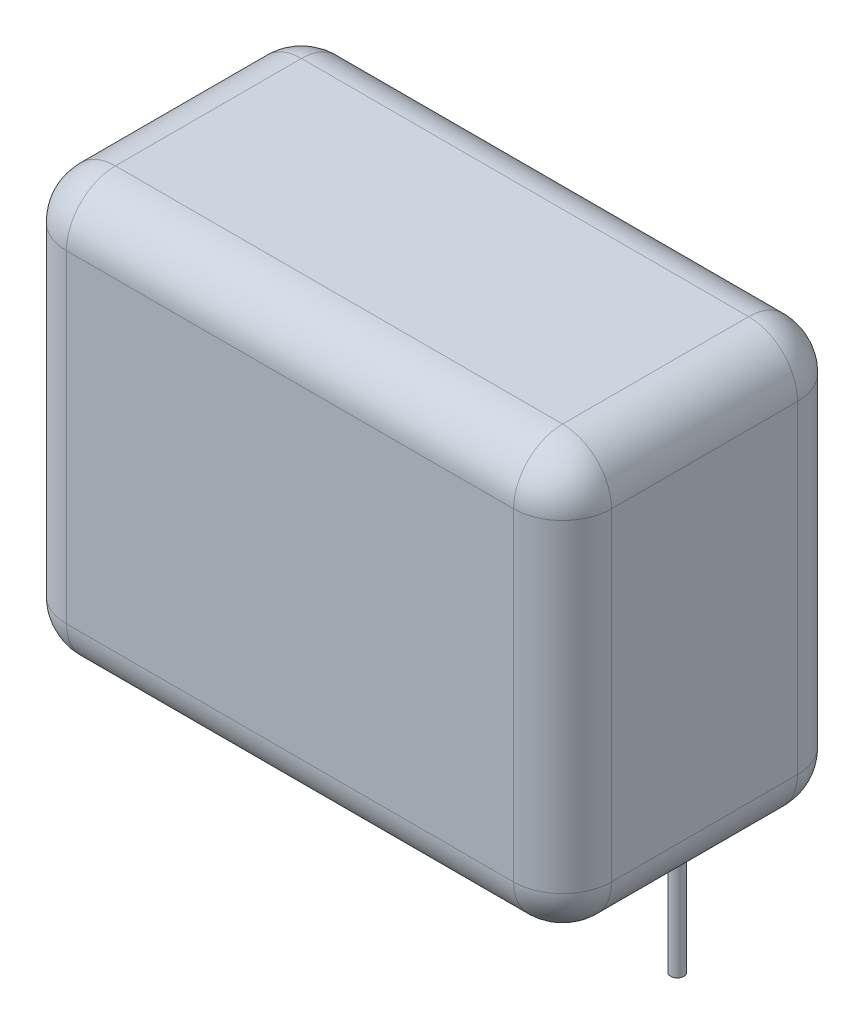
SolidWorks part; units mm, degrees
ref_plane "Front Plane" through (0, 0, 0) normal (0, 0, 1) x (1, 0, 0)
ref_plane "Top Plane" through (0, 0, 0) normal (0, 1, 0) x (1, 0, 0)
ref_plane "Right Plane" through (0, 0, 0) normal (1, 0, 0) x (0, 0, -1)
sketch "Sketch1" plane through (0, 0, 0) normal (1, 0, 0) x (0, 0, -1)
  line L1 (-5.7, 12.9) -> (5.7, 12.9)
  line L2 (-8.7, 9.9) -> (-8.7, -9.9)
  line L3 (-5.7, -12.9) -> (5.7, -12.9)
  line L4 (8.7, 9.9) -> (8.7, -9.9)
  line L5 (-8.7, 12.9) -> (8.7, -12.9) construction
  line L6 (-8.7, -12.9) -> (8.7, 12.9) construction
  arc A0 (-8.7, -9.9) -> (-5.7, -12.9) centre (-5.7, -9.9) ccw
  arc A1 (5.7, -12.9) -> (8.7, -9.9) centre (5.7, -9.9) ccw
  arc A2 (8.7, 9.9) -> (5.7, 12.9) centre (5.7, 9.9) ccw
  arc A3 (-5.7, 12.9) -> (-8.7, 9.9) centre (-5.7, 9.9) ccw
  point P0 (0, 0)
  dimension "D3" = 3
  dimension "D1" = 25.8
  dimension "D2" = 17.4
extrude "Boss-Extrude1" add sketch "Sketch1" along normal mid plane 33.4
fillet "Fillet1" radius 3 16 edges at (-16.7, -12.9, 0) (-16.7, -12.0213, -7.8213) (-16.7, 0, -8.7) (-16.7, 12.0213, -7.8213) (-16.7, 12.9, 0) (-16.7, 12.0213, 7.8213) (-16.7, 0, 8.7) (-16.7, -12.0213, 7.8213) (16.7, 0, 8.7) (16.7, 12.0213, 7.8213) (16.7, 12.9, 0) (16.7, 12.0213, -7.8213) (16.7, 0, -8.7) (16.7, -12.0213, -7.8213) (16.7, -12.9, 0) (16.7, -12.0213, 7.8213)
sketch "Sketch2" plane through (0, 0, 0) normal (0, 1, 0) x (1, 0, 0)
  line L0 (0, 4.8588) -> (0, -2.8425) construction
  circle A0 centre (15.03, 0) radius 0.4
  circle A1 centre (-15.03, 0) radius 0.4
  dimension "D1" = 0.8
  dimension "D2" = 15.03
extrude "Boss-Extrude2" add sketch "Sketch2" against normal blind 18.4
sketch "Sketch5" plane through (0, 0, -8.7) normal (0, 0, -1) x (-1, 0, 0)
  line L0 (-12.2924, -1.729) -> (11.884, -1.729) construction
  text T0 "10uF 400V" font "Century Gothic" height 3.5
extrude "Cut-Extrude1" cut sketch "Sketch5" against normal blind 0.01
